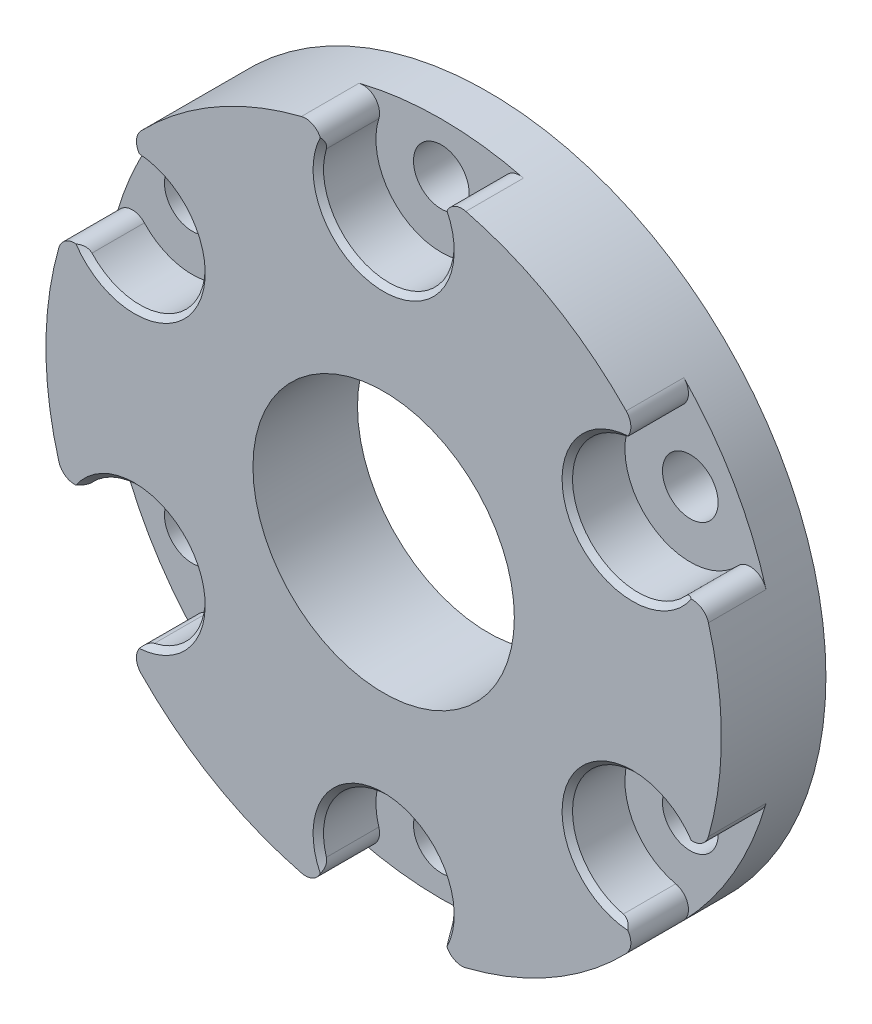
SolidWorks part; units mm, degrees
ref_plane "Front Plane" through (0, 0, 0) normal (0, 0, 1) x (1, 0, 0)
ref_plane "Top Plane" through (0, 0, 0) normal (0, 1, 0) x (1, 0, 0)
ref_plane "Right Plane" through (0, 0, 0) normal (1, 0, 0) x (0, 0, -1)
sketch "Sketch1" plane through (0, 0, 0) normal (0, 0, 1) x (1, 0, 0)
  circle A0 centre (0, 0) radius 41.021
  circle A1 centre (0, 34.925) radius 3.175
  circle A2 centre (0, 0) radius 34.925 construction
  circle A3 centre (30.2459, 17.4625) radius 3.175
  circle A4 centre (30.2459, -17.4625) radius 3.175
  circle A5 centre (0, -34.925) radius 3.175
  circle A6 centre (-30.2459, -17.4625) radius 3.175
  circle A7 centre (-30.2459, 17.4625) radius 3.175
  circle A8 centre (0, 0) radius 15.875
  point P18 (0, 0)
  dimension "D1" = 82.042
  dimension "D2" = 6.35
  dimension "D3" = 69.85
  dimension "D5" = 31.75
  dimension "D4" = 6
extrude "Boss-Extrude1" add sketch "Sketch1" along normal mid plane 12.7 contours A8 | A1 | A7 | A6 | A4 | A3 | A0 | A5
sketch "Sketch8" plane through (0, 0, 6.35) normal (0, 0, 1) x (1, 0, 0)
  circle A0 centre (-30.2459, -17.4625) radius 3.175 construction
  circle A1 centre (0, -34.925) radius 3.175 construction
  circle A2 centre (30.2459, -17.4625) radius 3.175 construction
  circle A3 centre (30.2459, 17.4625) radius 3.175 construction
  circle A4 centre (0, 34.925) radius 3.175 construction
  circle A5 centre (-30.2459, 17.4625) radius 3.175 construction
  circle A6 centre (-30.2459, -17.4625) radius 3.175
  circle A7 centre (0, -34.925) radius 3.175
  circle A8 centre (30.2459, -17.4625) radius 3.175
  circle A9 centre (30.2459, 17.4625) radius 3.175
  circle A10 centre (0, 34.925) radius 3.175
  circle A11 centre (-30.2459, 17.4625) radius 3.175
  point P0 (-30.2459, -17.4625)
  point P2 (0, -34.925)
  point P4 (30.2459, -17.4625)
  point P6 (30.2459, 17.4625)
  point P8 (0, 34.925)
  point P10 (-30.2459, 17.4625)
hole_wizard "CBORE for 1/4 Hex Machine Screw1" positions "Sketch8" profile "Sketch9" counterbore size "1/4" standard "ANSI Inch" end condition through all
sketch "Sketch9" plane through (-30.2459, -17.4625, 6.35) normal (1, 0, 0) x (0, -1, 0)
  line L0 (0, 0) -> (0, 12.7)
  line L1 (0, 12.7) -> (3.3782, 12.7)
  line L3 (3.3782, 12.7) -> (3.3782, 7)
  line L4 (7.9375, 7) -> (3.3782, 7)
  line L5 (7.9375, 7) -> (7.9375, 0.635)
  line L6 (7.9375, 0.635) -> (8.5725, 0)
  line L7 (8.5725, 0) -> (0, 0)
  line L8 (-7.9375, 0.635) -> (-8.5725, 0) construction
  line L11 (0, -6.35) -> (0, 107.95) construction
  dimension "Thru Hole Dia." = 6.7564
  dimension "Thru Hole Depth" = 12.7
  dimension "C'Bore Dia." = 15.875
  dimension "C'Bore Depth" = 7
  dimension "Near C'Sink Dia." = 17.145
  dimension "Near C'Sink Angle" = 90
fillet "Fillet1" radius 2 12 edges at (37.9533, -15.565, 2.5325) (32.4563, -25.086, 2.5325) (5.497, -40.651, 2.5325) (-5.497, -40.651, 2.5325) (-32.4563, -25.086, 2.5325) (-37.9533, -15.565, 2.5325) (32.4563, 25.086, 2.5325) (37.9533, 15.565, 2.5325) (-5.497, 40.651, 2.5325) (5.497, 40.651, 2.5325) (-37.9533, 15.565, 2.5325) (-32.4563, 25.086, 2.5325)
